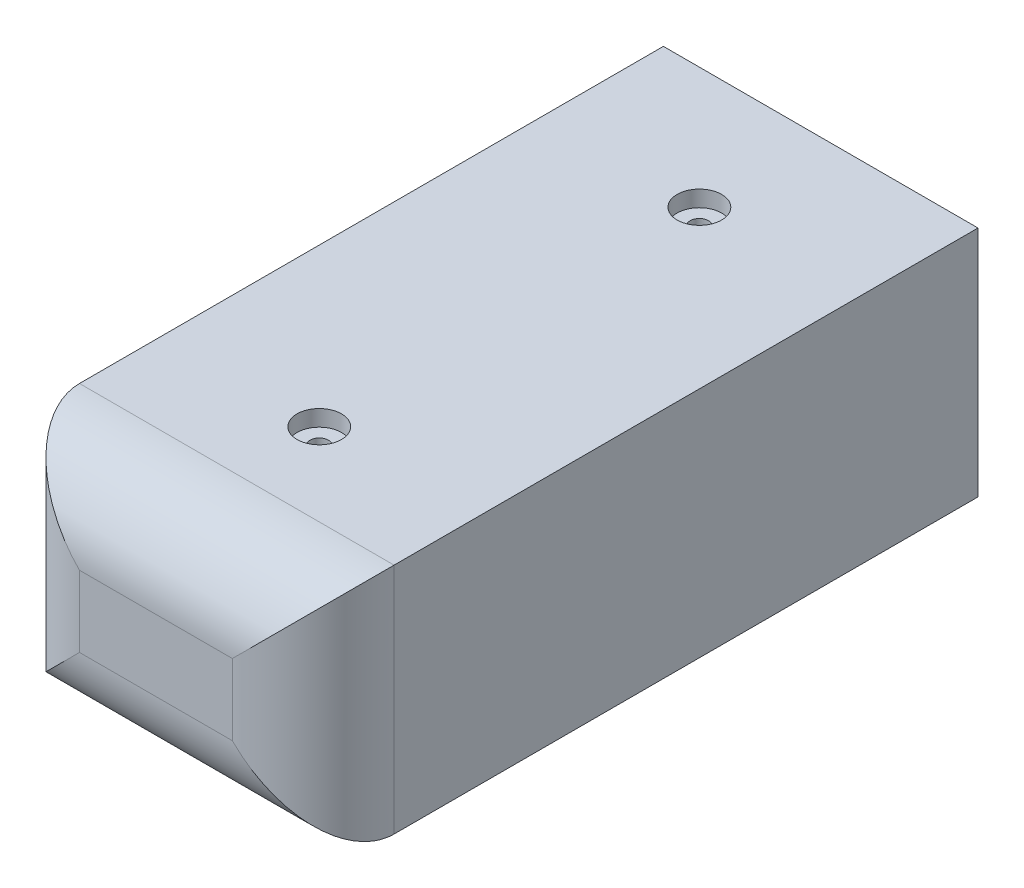
SolidWorks part; units mm, degrees
ref_plane "Ebene vorne" through (0, 0, 0) normal (0, 0, 1) x (1, 0, 0)
ref_plane "Ebene oben" through (0, 0, 0) normal (0, 1, 0) x (1, 0, 0)
ref_plane "Ebene rechts" through (0, 0, 0) normal (1, 0, 0) x (0, 0, -1)
sketch "Skizze1" plane through (0, 0, 0) normal (0, 0, 1) x (1, 0, 0)
  line L1 (77.8, -57.6) -> (-77.8, -57.6)
  line L2 (77.8, -57.6) -> (77.8, 57.6)
  line L3 (77.8, 57.6) -> (-77.8, 57.6)
  line L4 (-77.8, -57.6) -> (-77.8, 57.6)
  line L5 (77.8, -57.6) -> (-77.8, 57.6) construction
  line L6 (77.8, 57.6) -> (-77.8, -57.6) construction
  point P0 (0, 0)
  dimension "D1" = 115.2
  dimension "D2" = 155.6
extrude "Aufsatz-Linear austragen1" add sketch "Skizze1" along normal blind 328.8
sketch "Skizze2" plane through (77.8, 0, 0) normal (1, 0, 0) x (0, 0, -1)
  line L0 (-288.8, 57.6) -> (-212.3812, 57.6)
  line L1 (-328.8, 57.6) -> (0, 57.6) construction
  line L2 (-212.3812, 57.6) -> (-328.8, 118.2779)
  line L3 (-328.8, 118.2779) -> (-328.8, 17.6)
  line L4 (-328.8, -57.6) -> (-328.8, 57.6) construction
  arc A0 (-288.8, 57.6) -> (-328.8, 17.6) centre (-288.8, 17.6) ccw
  dimension "D1" = 40
extrude "Schnitt-Linear austragen1" cut sketch "Skizze2" against normal blind 328.8
mirror "Spiegeln1" about plane through (0, 0, 0) normal (0, 1, 0) of "Schnitt-Linear austragen1"
sketch "Skizze3" plane through (0, 57.6, 0) normal (0, 1, 0) x (1, 0, 0)
  line L0 (-77.8, -328.8) -> (-77.8, -288.8)
  line L1 (-77.8, -288.8) -> (-77.8, 0) construction
  line L2 (-77.8, -328.8) -> (-37.8, -328.8)
  arc A0 (-77.8, -288.8) -> (-37.8, -328.8) centre (-37.8, -288.8) ccw
  dimension "D1" = 40
extrude "Schnitt-Linear austragen2" cut sketch "Skizze3" against normal blind 328.8
mirror "Spiegeln2" about plane through (0, 0, 0) normal (1, 0, 0) of "Schnitt-Linear austragen2"
hole_wizard "Kernloch für M8x1.251" positions "Skizze5" profile "Skizze6" hole size "M8x1.25" standard "ANSI Metrisch"
sketch "Skizze5" plane through (0, 0, 0) normal (0, 0, -1) x (-1, 0, 0)
  point P0 (-47.8, 0)
  point P3 (47.8, 0)
sketch "Skizze6" plane through (47.8, 0, 0) normal (1, 0, 0) x (0, 1, 0)
  line L0 (0, 0) -> (0, 32.0429)
  line L1 (0, 32.0429) -> (3.4, 30)
  line L2 (3.4, 30) -> (3.4, 0)
  line L5 (3.4, 0) -> (0, 0)
  line L10 (0, 32.0429) -> (-3.4, 30) construction
  line L11 (0, -6.35) -> (0, 107.95) construction
  dimension "Bohrerdurchmesser" = 6.8
  dimension "Bohrungstiefe" = 30
  dimension "Spitzenwinkel" = 118
cosmetic thread "Gewindedarstellung3" parameters "D2"=10
cosmetic thread "Gewindedarstellung4" parameters "D2"=10
hole_wizard "Stirnsenkung für M8 Senkschraube (Kopf Button)1" positions "Skizze8" profile "Skizze7" counterbore size "M8" standard "ANSI Metrisch" end condition through all
sketch "Skizze8" plane through (0, 57.6, 0) normal (0, 1, 0) x (1, 0, 0)
  line L0 (77.8, 0) -> (-77.8, 0) construction
  point P0 (0, -248)
  point P2 (0, -60)
  dimension "D1" = 188
  dimension "D2" = 60
sketch "Skizze7" plane through (0, 57.6, 248) normal (1, 0, 0) x (0, 0, 1)
  line L0 (0, 0) -> (0, 115.2)
  line L1 (0, 115.2) -> (4.5, 115.2)
  line L3 (4.5, 115.2) -> (4.5, 8)
  line L4 (4.5, 8) -> (11, 8)
  line L5 (11, 8) -> (11, 0)
  line L7 (11, 0) -> (0, 0)
  line L11 (0, -6.35) -> (0, 107.95) construction
  dimension "Bohrerdurchmesser" = 9
  dimension "Bohrungstiefe" = 115.2
  dimension "Senkdurchmesser2" = 22
  dimension "Senktiefe2" = 8
hole_wizard "Stirnsenkung für M8 Senkschraube (Kopf Button)2" positions "Skizze10" profile "Skizze9" counterbore size "M8" standard "ANSI Metrisch" end condition through all
sketch "Skizze10" plane through (0, -57.6, 0) normal (0, -1, 0) x (-1, 0, 0)
  point P0 (0, -248)
  point P3 (0, -60)
sketch "Skizze9" plane through (0, -57.6, 248) normal (1, 0, 0) x (0, 0, -1)
  line L0 (0, 0) -> (0, 115.2)
  line L1 (0, 115.2) -> (4.5, 115.2)
  line L3 (4.5, 115.2) -> (4.5, 8)
  line L4 (4.5, 8) -> (7.5, 8)
  line L5 (7.5, 8) -> (7.5, 0)
  line L7 (7.5, 0) -> (0, 0)
  line L11 (0, -6.35) -> (0, 107.95) construction
  dimension "Bohrerdurchmesser" = 9
  dimension "Bohrungstiefe" = 115.2
  dimension "Senkdurchmesser2" = 15
  dimension "Senktiefe2" = 8
